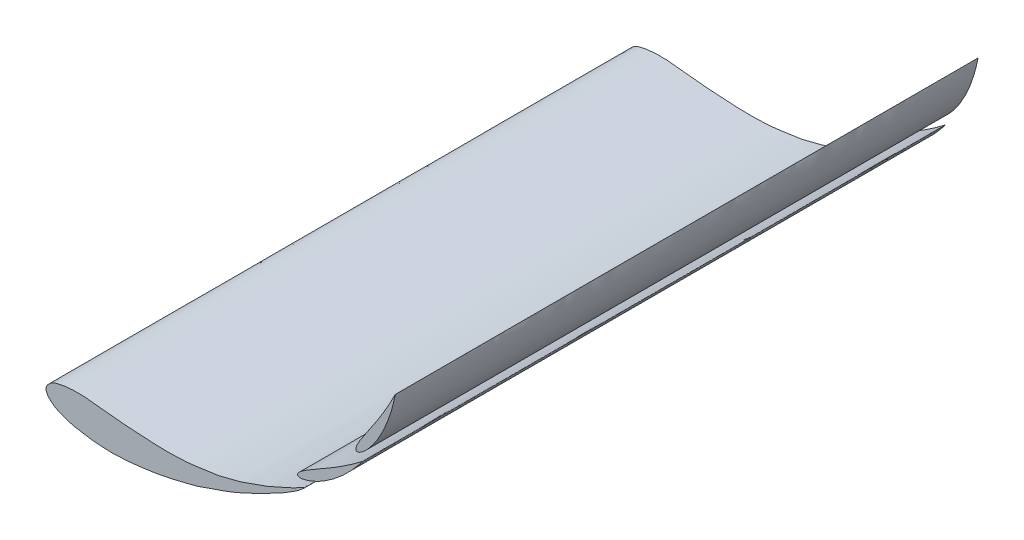
SolidWorks part; units mm, degrees
ref_plane "Front Plane" through (0, 0, 0) normal (0, 0, 1) x (1, 0, 0)
ref_plane "Top Plane" through (0, 0, 0) normal (0, 1, 0) x (1, 0, 0)
ref_plane "Right Plane" through (0, 0, 0) normal (1, 0, 0) x (0, 0, -1)
sketch "Sketch1" plane through (0, 0, 0) normal (0, 0, 1) x (1, 0, 0)
  line L0 (46.9575, 64.3181) -> (1074.8558, 208.7798) construction
sketch "Sketch2" plane through (0, 0, 0) normal (0, 0, 1) x (1, 0, 0)
  line L0 (0, 0) -> (400, 0) construction
  line L1 (0, 0) -> (399.6225, 66.8739) construction
  line L2 (0, 66.8739) -> (0, -66.8739) construction
  line L3 (10.0115, 66.8739) -> (10.0115, -116.1581) construction
  line L4 (20.0229, 66.8739) -> (20.0229, -116.1581) construction
  line L5 (30.0344, 66.8739) -> (30.0344, -116.1581) construction
  line L6 (40.0459, 66.8739) -> (40.0459, -116.1581) construction
  line L7 (50.0573, 66.8739) -> (50.0573, -116.1581) construction
  line L8 (60.0688, 66.8739) -> (60.0688, -116.1581) construction
  line L9 (70.0803, 66.8739) -> (70.0803, -116.1581) construction
  line L10 (80.0918, 66.8739) -> (80.0918, -116.1581) construction
  line L11 (90.1032, 66.8739) -> (90.1032, -116.1581) construction
  line L12 (100.1147, 66.8739) -> (100.1147, -116.1581) construction
  line L13 (110.1262, 66.8739) -> (110.1262, -116.1581) construction
  line L14 (120.1376, 66.8739) -> (120.1376, -116.1581) construction
  line L15 (130.1491, 66.8739) -> (130.1491, -116.1581) construction
  line L16 (140.1606, 66.8739) -> (140.1606, -116.1581) construction
  line L17 (150.172, 66.8739) -> (150.172, -116.1581) construction
  line L18 (160.1835, 66.8739) -> (160.1835, -116.1581) construction
  line L19 (170.195, 66.8739) -> (170.195, -116.1581) construction
  line L20 (180.2064, 66.8739) -> (180.2064, -116.1581) construction
  line L21 (190.2179, 66.8739) -> (190.2179, -116.1581) construction
  line L22 (200.2294, 66.8739) -> (200.2294, -116.1581) construction
  line L23 (210.2408, 66.8739) -> (210.2408, -116.1581) construction
  line L24 (220.2523, 66.8739) -> (220.2523, -116.1581) construction
  line L25 (230.2638, 66.8739) -> (230.2638, -116.1581) construction
  line L26 (240.2753, 66.8739) -> (240.2753, -116.1581) construction
  line L27 (250.2867, 66.8739) -> (250.2867, -116.1581) construction
  line L28 (260.2982, 66.8739) -> (260.2982, -116.1581) construction
  line L29 (270.3097, 66.8739) -> (270.3097, -116.1581) construction
  line L30 (280.3211, 66.8739) -> (280.3211, -116.1581) construction
  line L31 (290.3326, 66.8739) -> (290.3326, -116.1581) construction
  line L32 (300.3441, 66.8739) -> (300.3441, -116.1581) construction
  line L33 (310.3555, 66.8739) -> (310.3555, -116.1581) construction
  line L34 (320.367, 66.8739) -> (320.367, -116.1581) construction
  line L35 (330.3785, 66.8739) -> (330.3785, -116.1581) construction
  line L36 (340.3899, 66.8739) -> (340.3899, -116.1581) construction
  line L37 (350.4014, 66.8739) -> (350.4014, -116.1581) construction
  line L38 (360.4129, 66.8739) -> (360.4129, -116.1581) construction
  line L39 (370.4243, 66.8739) -> (370.4243, -116.1581) construction
  line L40 (380.4358, 66.8739) -> (380.4358, -116.1581) construction
  line L41 (390.4473, 66.8739) -> (390.4473, -116.1581) construction
  line L42 (400.4588, 66.8739) -> (400.4588, -116.1581) construction
  line L43 (836.1007, 66.8739) -> (-36.8556, 66.8739) construction
  line L44 (389.6225, 76.8739) -> (409.6225, 76.8739) construction
  line L45 (399.6225, 90.7703) -> (399.6225, 62.9774) construction
  line L46 (539.2399, 261.0337) -> (478.7399, 156.2446) construction
  line L47 (488.7399, 146.2766) -> (482.6971, 142.1346) construction
  line L48 (389.6225, 76.8739) -> (488.7399, 146.2766) construction
  line L51 (488.7399, 194.8045) -> (488.7399, 123.7678) construction
  line L52 (478.7399, 201.6203) -> (478.7399, 116.9521) construction
  line L53 (478.7399, 156.2446) -> (614.5057, 156.2446) construction
  line L54 (389.6225, 83.3039) -> (389.6225, -27.4023) construction
  line L55 (478.7399, 146.2446) -> (614.5057, 146.2446) construction
  spline S0 degree 3 poles (8.4176, 12.2629) (-5.1, -0.6947) (8.0175, -15.4806) (19.5512, -21.724) (30.0167, -25.3022) (39.86, -28.8642) (50.0404, -30.6629) (60.0706, -32.2577) (70.0139, -34.2177) (80.101, -34.56) (90.0931, -35.3652) (100.112, -35.9529) (110.1282, -35.5072) (120.1532, -35.21) (130.1503, -34.2298) (140.19, -33.4102) (150.1782, -31.9134) (160.1704, -30.3713) (170.2408, -29.1636) (180.2083, -27.151) (190.2638, -25.3061) (200.2392, -22.8725) (210.2446, -20.4291) (220.2329, -17.8951) (230.3811, -15.7054) (240.3519, -12.3911) (253.5512, -7.3696) (266.9476, -2.8065) (280.4369, 1.6366) (290.3614, 5.8195) (300.4407, 10.0322) (310.3048, 14.8841) (323.8214, 20.8842) (337.3023, 27.2498) (350.2747, 34.8502) (364.0374, 41.2007) (378.0734, 50.4319) (389.2687, 56.9917) (404.9331, 70.6704) (388.8931, 60.8973) (380.9617, 56.8333) (370.3166, 52.1732) (360.4136, 47.7491) (350.4697, 43.0754) (340.4967, 38.8332) (330.4052, 35.261) (320.3498, 31.8494) (310.3583, 28.3259) (300.4869, 24.6622) (290.3218, 22.3006) (280.2904, 19.7619) (270.4267, 16.765) (260.336, 15.0613) (250.2769, 13.9588) (240.2662, 12.5783) (230.2787, 11.0679) (220.2867, 9.6964) (210.2433, 9.2404) (200.2287, 9.0345) (190.217, 8.2792) (180.2125, 9.1624) (170.1842, 8.7285) (160.1865, 9.5822) (150.1678, 9.9892) (140.1635, 10.7007) (130.146, 11.2145) (120.1214, 11.8409) (110.1328, 12.9697) (100.1148, 13.8501) (90.0938, 14.7159) (80.0796, 15.8427) (56.9177, 18.8475) (32.3828, 18.9634) (8.4176, 12.2629) (-5.1, -0.6947) (8.0175, -15.4806) knots -0.089629 -0.030705 -0.018228 0 0.022024 0.035622 0.048197 0.060585 0.072602 0.084545 0.096479 0.108284 0.12009 0.131879 0.143661 0.155449 0.167269 0.1791 0.190991 0.202897 0.214788 0.226766 0.238768 0.250864 0.262992 0.27512 0.287235 0.299601 0.31215 0.337082 0.349542 0.362249 0.375072 0.388091 0.40103 0.427261 0.440709 0.453892 0.481344 0.495528 0.510184 0.522428 0.535733 0.548643 0.561554 0.574511 0.587287 0.599816 0.612271 0.624763 0.637218 0.649381 0.661544 0.67375 0.685718 0.697586 0.709472 0.721375 0.733243 0.74504 0.756824 0.768611 0.780398 0.792175 0.803972 0.815766 0.827567 0.839363 0.851169 0.863006 0.874833 0.88666 0.89851 0.910371 0.969295 0.981772 1 1.022024 1.035622 1.048197 only from (0, 0) to (0, 0)
  spline S1 degree 3 poles (488.4807, 145.9571) (488.8121, 146.3498) (488.4243, 146.015) (488.0622, 145.7851) (487.2625, 145.1263) (486.2197, 144.3713) (484.8735, 143.3367) (483.2507, 142.1161) (481.3449, 140.7026) (479.1839, 139.1083) (476.7613, 137.3643) (474.1237, 135.4494) (471.2368, 133.4393) (468.1657, 131.2913) (464.8962, 129.0676) (461.4575, 126.7695) (457.874, 124.4106) (454.1513, 122.027) (450.3296, 119.6083) (446.4184, 117.1921) (442.4423, 114.7926) (438.4319, 112.4153) (434.4211, 110.0589) (430.4193, 107.7484) (426.4691, 105.4752) (422.5724, 103.27) (418.7829, 101.1054) (415.1038, 99.0189) (411.5811, 96.98) (408.2231, 95.0247) (405.0701, 93.1172) (402.1178, 91.3128) (399.4157, 89.5543) (396.9653, 87.8935) (394.7924, 86.3186) (392.9158, 84.83) (391.3498, 83.4309) (390.0835, 82.1509) (389.1526, 80.9646) (388.5665, 79.872) (388.3105, 78.8689) (388.4525, 77.9475) (389.0134, 77.2045) (389.9156, 76.685) (391.1282, 76.3842) (392.6501, 76.2546) (394.4851, 76.3138) (396.6232, 76.5794) (399.0459, 77.0357) (401.7358, 77.7205) (404.6757, 78.5968) (407.8392, 79.7049) (411.2008, 81.0269) (414.7209, 82.591) (418.3956, 84.3418) (422.1799, 86.3091) (426.0457, 88.48) (429.9704, 90.8288) (433.915, 93.3645) (437.8712, 96.0402) (441.7934, 98.8661) (445.6685, 101.7972) (449.4657, 104.8272) (453.1679, 107.924) (456.7615, 111.054) (460.2029, 114.2195) (463.5191, 117.343) (466.6501, 120.455) (469.6136, 123.4898) (472.3702, 126.4509) (474.954, 129.2656) (477.2978, 131.9605) (479.4562, 134.4635) (481.3811, 136.7846) (483.0779, 138.8974) (484.5577, 140.7696) (485.8099, 142.3825) (486.8479, 143.7389) (487.6258, 144.7686) (488.2511, 145.5957) (488.4807, 145.9571) (488.8121, 146.3498) (488.4243, 146.015) knots -0.00692 -0.003098 -0.00077 0 0.000781 0.003074 0.006931 0.012248 0.01903 0.027226 0.036785 0.04761 0.059602 0.072764 0.086897 0.102004 0.117939 0.134556 0.151858 0.169651 0.187838 0.206374 0.225065 0.243814 0.262569 0.281137 0.299514 0.317506 0.335105 0.352118 0.368488 0.384167 0.398955 0.412906 0.425872 0.437811 0.448585 0.458213 0.466669 0.473884 0.479894 0.484779 0.488743 0.492167 0.495628 0.499576 0.504487 0.510576 0.517943 0.526574 0.536524 0.54764 0.560015 0.573491 0.588031 0.603544 0.619912 0.637089 0.654944 0.673346 0.692212 0.711461 0.73091 0.750475 0.770022 0.789461 0.808651 0.827458 0.84582 0.863559 0.880666 0.896945 0.912322 0.926718 0.939993 0.952161 0.96306 0.972662 0.980906 0.987733 0.99308 0.996902 0.99923 1 1.000781 1.003074 1.006931 only from (488.7399, 146.2766) to (488.7399, 146.2766)
  spline S2 degree 3 poles (539.1474, 260.6327) (539.2727, 261.1311) (539.0712, 260.66) (538.847, 260.2944) (538.4178, 259.3511) (537.8126, 258.2147) (537.0576, 256.6938) (536.1358, 254.8842) (535.0445, 252.777) (533.8032, 250.3953) (532.3928, 247.7642) (530.8643, 244.8851) (529.1535, 241.8109) (527.3379, 238.5318) (525.3773, 235.0977) (523.2973, 231.5223) (521.114, 227.8287) (518.8164, 224.0518) (516.4453, 220.1998) (513.9926, 216.3108) (511.4744, 212.4083) (508.9156, 208.5106) (506.3472, 204.6315) (503.7668, 200.7977) (501.2162, 197.0199) (498.684, 193.3269) (496.2302, 189.7174) (493.8413, 186.2265) (491.572, 182.8471) (489.4139, 179.6152) (487.4191, 176.5163) (485.5592, 173.5982) (483.904, 170.8313) (482.432, 168.2626) (481.1716, 165.8931) (480.1395, 163.7313) (479.3471, 161.7863) (478.7717, 160.08) (478.4564, 158.6052) (478.4098, 157.3661) (478.6205, 156.3524) (479.1528, 155.587) (479.9832, 155.1657) (481.022, 155.0953) (482.2436, 155.3578) (483.6679, 155.9099) (485.2905, 156.7692) (487.0948, 157.9471) (489.0711, 159.4214) (491.187, 161.2183) (493.4434, 163.297) (495.7989, 165.6824) (498.2384, 168.3469) (500.714, 171.2985) (503.2464, 174.4858) (505.7822, 177.9159) (508.3018, 181.5646) (510.7961, 185.3989) (513.2262, 189.41) (515.6053, 193.552) (517.8878, 197.8139) (520.0818, 202.1497) (522.1624, 206.5401) (524.1282, 210.9489) (525.9819, 215.3396) (527.6833, 219.6955) (529.2906, 223.9586) (530.7366, 228.1301) (532.0659, 232.1586) (533.2418, 236.03) (534.3267, 239.6939) (535.2487, 243.1448) (536.0884, 246.3418) (536.7982, 249.2728) (537.3945, 251.9164) (537.9016, 254.2486) (538.3181, 256.2478) (538.6549, 257.9225) (538.9014, 259.1894) (539.0999, 260.2071) (539.1474, 260.6327) (539.2727, 261.1311) (539.0712, 260.66) knots -0.00692 -0.003098 -0.00077 0 0.000781 0.003074 0.006931 0.012248 0.01903 0.027226 0.036785 0.04761 0.059602 0.072764 0.086897 0.102004 0.117939 0.134556 0.151858 0.169651 0.187838 0.206374 0.225065 0.243814 0.262569 0.281137 0.299514 0.317506 0.335105 0.352118 0.368488 0.384167 0.398955 0.412906 0.425872 0.437811 0.448585 0.458213 0.466669 0.473884 0.479894 0.484779 0.488743 0.492167 0.495628 0.499576 0.504487 0.510576 0.517943 0.526574 0.536524 0.54764 0.560015 0.573491 0.588031 0.603544 0.619912 0.637089 0.654944 0.673346 0.692212 0.711461 0.73091 0.750475 0.770022 0.789461 0.808651 0.827458 0.84582 0.863559 0.880666 0.896945 0.912322 0.926718 0.939993 0.952161 0.96306 0.972662 0.980906 0.987733 0.99308 0.996902 0.99923 1 1.000781 1.003074 1.006931 only from (539.2399, 261.0337) to (539.2399, 261.0337)
  point P7 (0, 0)
  point P94 (399.6225, 76.8739)
  point P100 (399.6225, 76.8739)
  point P108 (399.6225, 66.8739)
  point P110 (0, 0)
  point P112 (389.6225, 76.8739)
  point P114 (566.4739, 214.8677)
  point P126 (488.7399, 146.2766)
  point P130 (488.7399, 156.2766)
  point P136 (488.7399, 159.2862)
  point P142 (478.7399, 159.2862)
  point P146 (562.65, 212.2203)
  point P150 (484.4419, 143.2671)
  point P152 (475.2528, 156.2766)
  dimension "D1" = 9.5
  dimension "D3" = 405.1793
  dimension "D4" = 400
  dimension "D5" = 121
  dimension "D6" = 10
  dimension "D7" = 35
  dimension "D8" = 10
  dimension "D9" = 60
  dimension "D10" = 10
  dimension "D11" = 121
  dimension "D12" = 10
  dimension "D13" = 79.3707
  dimension "D2" = 41
extrude "Boss-Extrude1" add sketch "Sketch2" along normal blind 900
